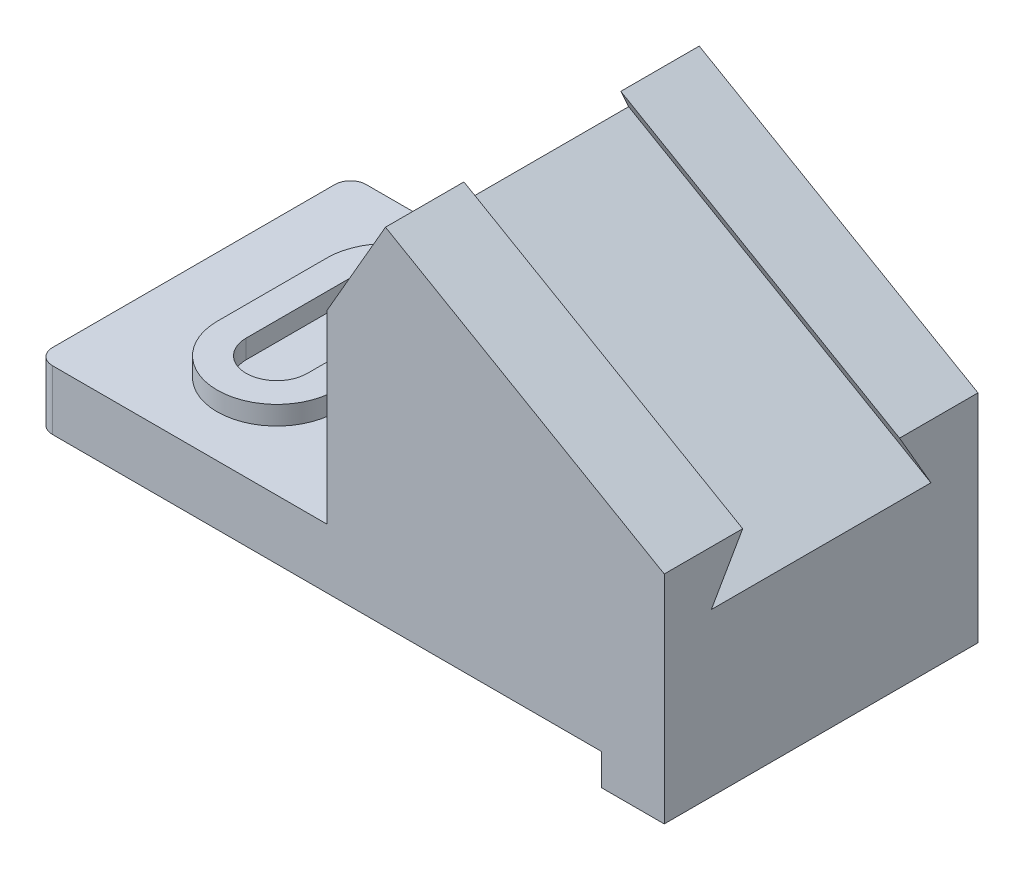
SolidWorks part; units mm, degrees
ref_plane "Front Plane" through (0, 0, 0) normal (0, 0, 1) x (1, 0, 0)
ref_plane "Top Plane" through (0, 0, 0) normal (0, 1, 0) x (1, 0, 0)
ref_plane "Right Plane" through (0, 0, 0) normal (1, 0, 0) x (0, 0, -1)
sketch "Sketch1" plane through (0, 0, 0) normal (0, 0, 1) x (1, 0, 0)
  line L0 (0, 0) -> (360, 0)
  line L1 (360, 0) -> (360, -20)
  line L2 (360, -20) -> (400, -20)
  line L3 (400, -20) -> (400, 118)
  line L4 (400, 118) -> (222.2955, 220.5977)
  line L5 (222.2955, 220.5977) -> (185, 156)
  line L6 (185, 156) -> (185, 38)
  line L7 (185, 38) -> (0, 38)
  line L8 (0, 38) -> (0, 0)
  line L9 (400, 113.3638) -> (400, 195.7817) construction
  dimension "D1" = 400
  dimension "D2" = 40
  dimension "D3" = 20
  dimension "D4" = 138
  dimension "D5" = 38
  dimension "D6" = 118
  dimension "D7" = 60
  dimension "D8" = 90
  dimension "D9" = 215
extrude "Boss-Extrude1" add sketch "Sketch1" along normal blind 200
sketch "Sketch2" plane through (71.2, -41.1073, 0) normal (-0.866, 0.5, 0) x (0, 0, 1)
  line L0 (30, 272.191) -> (170, 272.191)
  line L1 (100, 302.191) -> (100, 227.6) construction
  line L3 (200, 302.191) -> (0, 302.191) construction
  line L4 (200, 227.6) -> (0, 227.6) construction
  line L5 (50, 302.191) -> (150, 302.191)
  line L6 (50, 302.191) -> (30, 272.191)
  line L7 (150, 302.191) -> (170, 272.191)
  point P8 (100, 272.191)
  point P12 (100, 302.191)
  dimension "D1" = 100
  dimension "D2" = 140
  dimension "D3" = 30
extrude "Cut-Extrude1" cut sketch "Sketch2" against normal through all
fillet "Fillet1" radius 10 2 edges at (0, 19, 0) (0, 19, 200)
sketch "Sketch3" plane through (0, 38, 0) normal (0, 1, 0) x (1, 0, 0)
  line L0 (50, -135) -> (50, -65)
  line L7 (126, -135) -> (126, -65)
  line L8 (68.5, -135) -> (68.5, -65)
  line L10 (0, -190) -> (0, -10) construction
  line L12 (107.5, -135) -> (107.5, -65)
  arc A2 (126, -65) -> (50, -65) centre (88, -65) ccw
  arc A4 (50, -135) -> (126, -135) centre (88, -135) ccw
  arc A5 (107.5, -65) -> (68.5, -65) centre (88, -65) ccw
  arc A6 (68.5, -135) -> (107.5, -135) centre (88, -135) ccw
  point P1 (88, -100)
  point P8 (88, -100)
  point P11 (0, -100)
  dimension "D3" = 76
  dimension "D4" = 39
  dimension "D1" = 70
  dimension "D2" = 88
extrude "Boss-Extrude2" add sketch "Sketch3" along normal blind 12
